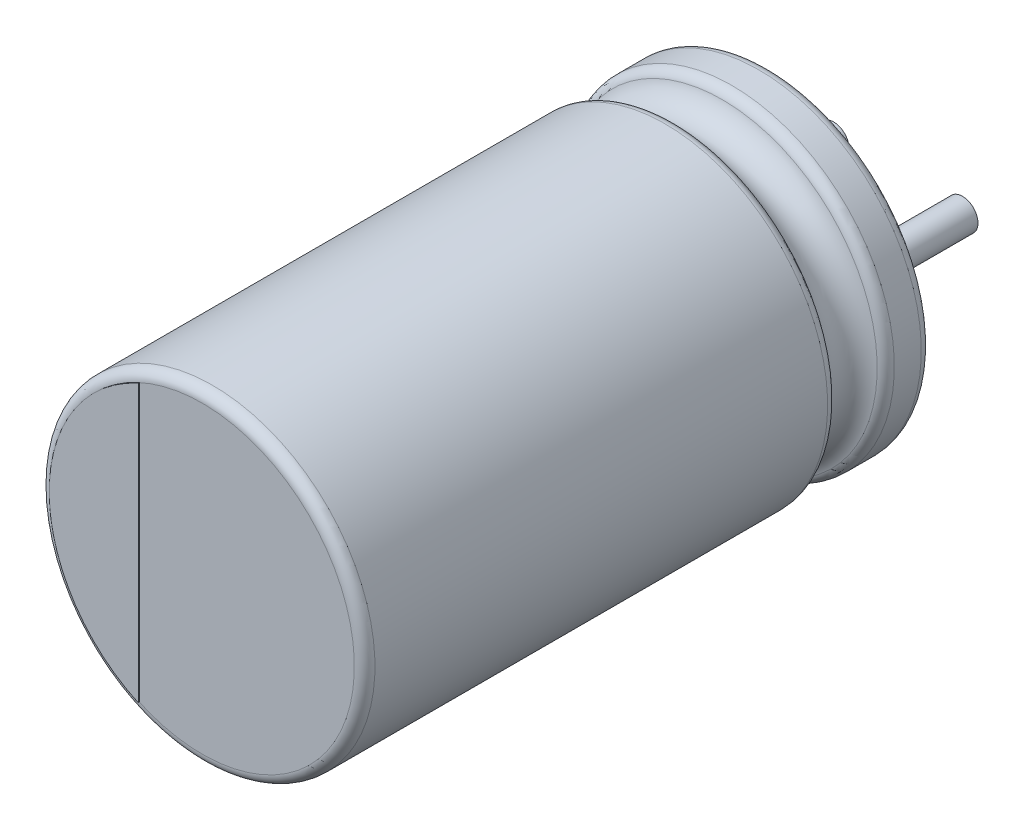
SolidWorks part; units mm, degrees
ref_plane "Спереди" through (0, 0, 0) normal (0, 0, 1) x (1, 0, 0)
ref_plane "Сверху" through (0, 0, 0) normal (0, 1, 0) x (1, 0, 0)
ref_plane "Справа" through (0, 0, 0) normal (1, 0, 0) x (0, 0, -1)
sketch "Эскиз1" plane through (0, 0, 0) normal (0, 1, 0) x (1, 0, 0)
  line L0 (0, 0) -> (0, -10.8304) construction
  line L1 (-3.15, -2.0173) -> (-3.15, -10.8)
  line L2 (0, 0) -> (-2.95, 0)
  line L3 (0, 0) -> (0, -11)
  line L4 (0, -11) -> (-2.95, -11)
  line L5 (-3.15, -0.2) -> (-3.15, -0.7235)
  line L6 (0, 0) -> (-3.15, -11) construction
  line L7 (0, -11) -> (-3.15, 0) construction
  arc A0 (-3.0091, -1.8262) -> (-3.0091, -0.9146) centre (-3.15, -1.3704) ccw
  arc A1 (-2.95, -11) -> (-3.15, -10.8) centre (-2.95, -10.8) cw
  arc A2 (-2.95, 0) -> (-3.15, -0.2) centre (-2.95, -0.2) ccw
  arc A3 (-3.0091, -0.9146) -> (-3.15, -0.7235) centre (-2.95, -0.7235) cw
  arc A4 (-3.0091, -1.8262) -> (-3.15, -2.0173) centre (-2.95, -2.0173) ccw
  point P6 (-1.575, -5.5)
  point P20 (-3.15, -1.8475)
  dimension "D3" = 0.2
  dimension "D1" = 11
  dimension "D2" = 3.15
  dimension "D4" = 0.9146
revolve "Повернуть1" add sketch "Эскиз1" angle 360 about L0
sketch "Эскиз2" plane through (0, 0, 0) normal (0, 0, 1) x (1, 0, 0)
  line L0 (-3.3257, 0) -> (3.3257, 0) construction
  line L1 (0, -3.465) -> (0, 3.465) construction
  circle A0 centre (1.25, 0) radius 0.3
  circle A1 centre (-1.25, 0) radius 0.3
  point P4 (0, 0)
  dimension "D1" = 2.5
  dimension "D2" = 0.6
extrude "Бобышка-Вытянуть1" add sketch "Эскиз2" against normal blind 2.5 separate body
sketch "Эскиз3" plane through (0, 0, 11) normal (0, 0, 1) x (1, 0, 0)
  line L2 (-1.2224, 2.6848) -> (-1.2224, -2.6848)
  line L3 (-1.2224, 2.6848) -> (0, 0) construction
  line L4 (0, 0) -> (-1.2224, -2.6848) construction
  line L5 (-1.2224, 0) -> (2.3909, 0) construction
  arc A2 (-1.2224, 2.6848) -> (-1.2224, -2.6848) centre (0, 0) ccw
  dimension "D1" = 2.95
extrude "Бобышка-Вытянуть2" add sketch "Эскиз3" along normal blind 0.02 separate body
